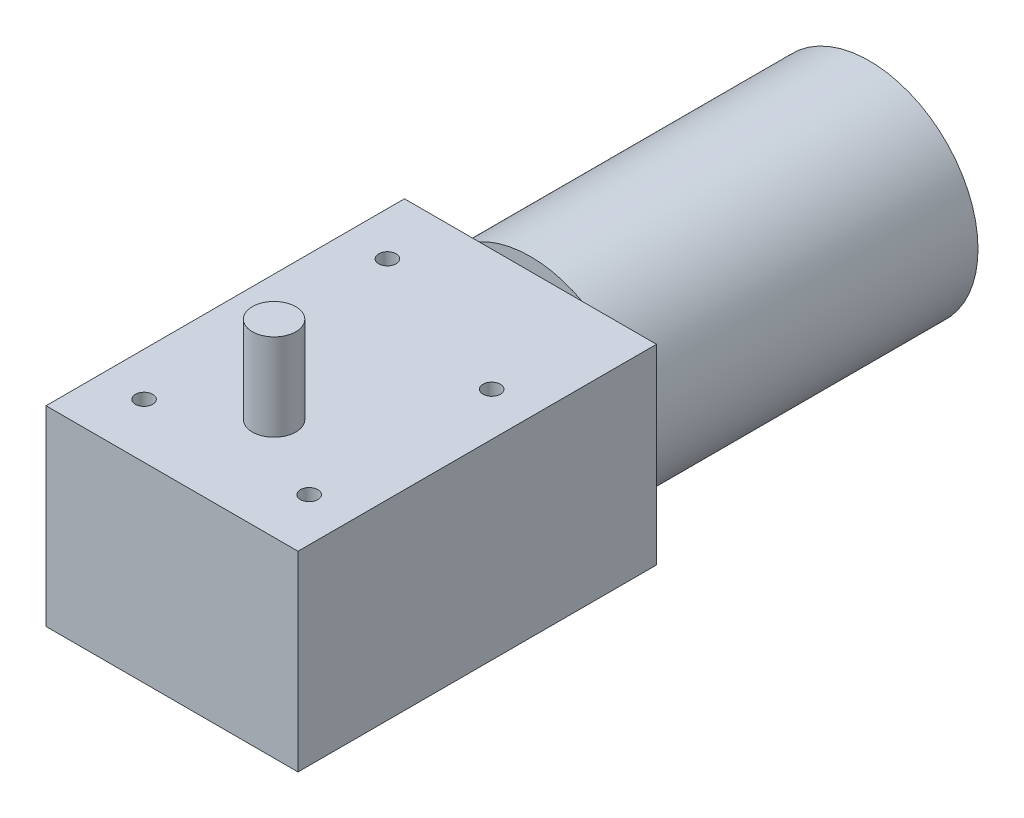
SolidWorks part; units mm, degrees
material "1023 Carbon Steel Sheet (SS)"
ref_plane "Front Plane" through (0, 0, 0) normal (0, 0, 1) x (1, 0, 0)
ref_plane "Top Plane" through (0, 0, 0) normal (0, 1, 0) x (1, 0, 0)
ref_plane "Right Plane" through (0, 0, 0) normal (1, 0, 0) x (0, 0, -1)
sketch "Sketch1" plane through (0, 0, 0) normal (0, 0, 1) x (1, 0, 0)
  circle A0 centre (0, 0) radius 25
  dimension "D1" = 50
extrude "Boss-Extrude1" add sketch "Sketch1" along normal blind 78
sketch "Sketch2" plane through (0, 0, 78) normal (0, 0, 1) x (1, 0, 0)
  line L1 (-29, -22) -> (29, -22)
  line L2 (-29, -22) -> (-29, 22)
  line L3 (-29, 22) -> (29, 22)
  line L4 (29, -22) -> (29, 22)
  circle A1 centre (0, 0) radius 25 construction
  point P4 (0, -22)
  point P6 (0, -25)
  dimension "D3" = 3
  dimension "D1" = 58
  dimension "D2" = 44
extrude "Boss-Extrude2" add sketch "Sketch2" along normal blind 82.5 contours L3 L4 L1 L2
sketch "Sketch3" plane through (0, 22, 0) normal (0, 1, 0) x (1, 0, 0)
  line L0 (-29, -160.5) -> (29, -160.5) construction
  circle A0 centre (0, -137) radius 5
  dimension "D2" = 10
  dimension "D1" = 23.5
extrude "Boss-Extrude3" add sketch "Sketch3" along normal blind 20
sketch "Sketch4" plane through (0, 22, 0) normal (0, 1, 0) x (1, 0, 0)
  line L2 (-19, -105.92) -> (19, -105.92)
  line L3 (-19, -105.92) -> (-19, -147.94)
  line L4 (-19, -147.94) -> (19, -147.94)
  line L5 (19, -105.92) -> (19, -147.94)
  circle A0 centre (0, -137) radius 5 construction
  circle A1 centre (0, -137) radius 5
  circle A2 centre (19, -147.94) radius 2
  circle A4 centre (19, -105.92) radius 2
  circle A6 centre (-19, -147.94) radius 2
  circle A7 centre (-19, -91.93) radius 2
  point P3 (0, -147.94)
  dimension "D4" = 4
  dimension "D1" = 42.02
  dimension "D2" = 38
  dimension "D3" = 10.94
  dimension "D5" = 45.07
extrude "Cut-Extrude1" cut sketch "Sketch4" against normal through all contours A7
